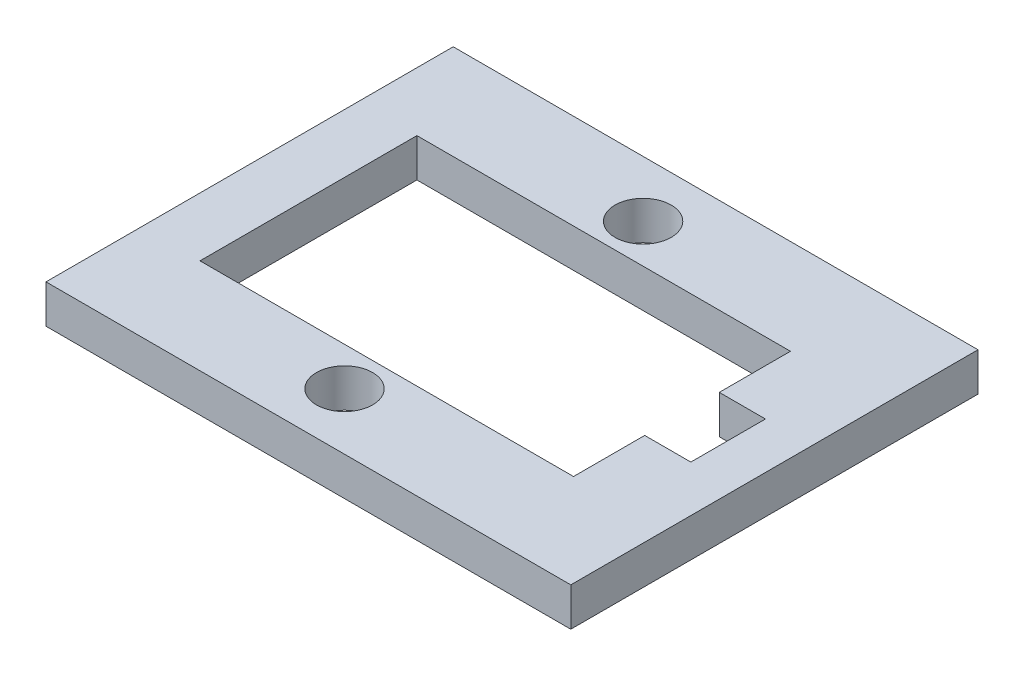
SolidWorks part; units mm, degrees
ref_plane "Front Plane" through (0, 0, 0) normal (0, 0, 1) x (1, 0, 0)
ref_plane "Top Plane" through (0, 0, 0) normal (0, 1, 0) x (1, 0, 0)
ref_plane "Right Plane" through (0, 0, 0) normal (1, 0, 0) x (0, 0, -1)
sketch "Sketch2" plane through (0, 0, 0) normal (0, 1, 0) x (1, 0, 0)
  line L0 (-12.8784, 7.8335) -> (11.4112, 7.8335)
  line L1 (-16.7015, 14.0166) -> (17.4229, 14.0166)
  line L2 (-16.7015, 14.0166) -> (-16.7015, -12.4616)
  line L3 (-16.7015, -12.4616) -> (17.4229, -12.4616)
  line L4 (17.4229, 14.0166) -> (17.4229, -12.4616)
  line L5 (11.4112, 7.8335) -> (11.4112, 3.2059)
  line L6 (11.4112, 3.2059) -> (14.4112, 3.2059)
  line L7 (14.4112, 3.2059) -> (14.4112, -1.6439)
  line L8 (14.4112, -1.6439) -> (11.4112, -1.6439)
  line L9 (11.4112, -1.6439) -> (11.4112, -6.2716)
  line L10 (11.4112, -6.2716) -> (-12.8784, -6.2716)
  line L11 (-12.8784, -6.2716) -> (-12.8784, 7.8335)
  circle A0 centre (-0.7026, 10.3665) radius 1.825
  circle A1 centre (-0.978, -8.7735) radius 1.825
  dimension "D8" = 3.65
  dimension "D1" = 19.14
  dimension "D3" = 4.6277
  dimension "D4" = 24.2896
  dimension "D5" = 3
  dimension "D6" = 4.8498
extrude "Boss-Extrude1" add sketch "Sketch2" along normal mid plane 2.5
